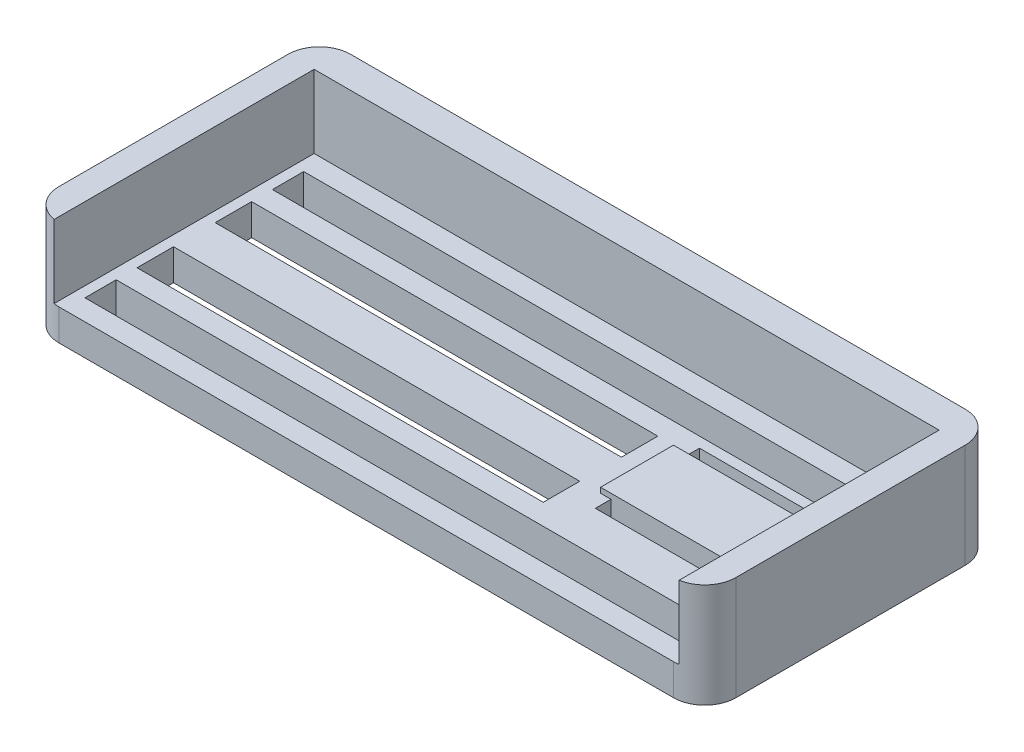
SolidWorks part; units mm, degrees
ref_plane "Front Plane" through (0, 0, 0) normal (0, 0, 1) x (1, 0, 0)
ref_plane "Top Plane" through (0, 0, 0) normal (0, 1, 0) x (1, 0, 0)
ref_plane "Right Plane" through (0, 0, 0) normal (1, 0, 0) x (0, 0, -1)
sketch "Sketch1" plane through (0, 0, 0) normal (0, 1, 0) x (1, 0, 0)
  line L1 (32.5, -14) -> (-32.5, -14)
  line L2 (32.5, -14) -> (32.5, 14)
  line L3 (32.5, 14) -> (-32.5, 14)
  line L4 (-32.5, -14) -> (-32.5, 14)
  line L5 (32.5, -14) -> (-32.5, 14) construction
  line L6 (32.5, 14) -> (-32.5, -14) construction
  point P0 (0, 0)
  dimension "D1" = 65
  dimension "D2" = 28
extrude "Boss-Extrude1" add sketch "Sketch1" along normal blind 10
sketch "Sketch2" plane through (0, 10, 0) normal (0, 1, 0) x (1, 0, 0)
  line L0 (-32.5, -14) -> (32.5, -14) construction
  line L2 (30, -11) -> (30, 11)
  line L3 (30, 11) -> (-30, 11)
  line L4 (-30, -11) -> (-30, 11)
  line L5 (30, -11) -> (-30, 11) construction
  line L6 (30, 11) -> (-30, -11) construction
  line L8 (-30, -11) -> (-30, -14)
  line L9 (-30, -14) -> (30, -14)
  line L10 (30, -11) -> (30, -14)
  point P0 (0, 0)
  dimension "D1" = 60
  dimension "D2" = 22
  dimension "D3" = 3
extrude "Cut-Extrude1" cut sketch "Sketch2" against normal blind 7
sketch "Sketch3" plane through (0, 3, 0) normal (0, 1, 0) x (1, 0, 0)
  line L0 (30, 0) -> (-30, 0) construction
  line L1 (30, -11) -> (-30, -11) construction
  line L2 (30, -11) -> (30, 11) construction
  line L3 (30, 11) -> (-30, 11) construction
  line L4 (-30, -11) -> (-30, 11) construction
  line L5 (30, -11) -> (-30, 11) construction
  line L6 (30, 11) -> (-30, -11) construction
  line L8 (23, -5) -> (13, -5)
  line L9 (23, -5) -> (23, 5)
  line L10 (23, 5) -> (13, 5)
  line L11 (13, -5) -> (13, 5)
  line L12 (23, -5) -> (13, 5) construction
  line L13 (23, 5) -> (13, -5) construction
  point P0 (0, 0)
  point P8 (18, 0)
  dimension "D1" = 60
  dimension "D2" = 22
  dimension "D3" = 10
  dimension "D4" = 10
  dimension "D5" = 7
extrude "Cut-Extrude2" cut sketch "Sketch3" against normal blind 7
ref_plane "Plane1" through (18, 0, 0) normal (1, 0, 0) x (0, 0, -1)
sketch "Sketch4" plane through (18, 0, 0) normal (1, 0, 0) x (0, 0, -1)
  line L0 (-3.5, -3.5) -> (-2.1213, -2.1213)
  line L2 (3.5, -3.5) -> (3.5, 3.5)
  line L3 (3.5, 3.5) -> (-3.5, 3.5)
  line L4 (-3.5, -3.5) -> (-3.5, 3.5)
  line L5 (3.5, -3.5) -> (-3.5, 3.5) construction
  line L6 (3.5, 3.5) -> (-3.5, -3.5) construction
  line L7 (2.1213, -2.1213) -> (3.5, -3.5)
  arc A0 (2.1213, -2.1213) -> (-2.1213, -2.1213) centre (0, 0) ccw
  point P0 (0, 0)
  dimension "D3" = 6
  dimension "D1" = 7
  dimension "D2" = 7
extrude "Boss-Extrude5" add sketch "Sketch4" along normal mid plane 12
sketch "Sketch5" plane through (23, 0, 0) normal (-1, 0, 0) x (0, 0, 1)
  line L2 (-2.8983, 0.1) -> (2.8983, 0.1)
  line L3 (-2.8983, 0.1) -> (2.8983, 0.1)
  arc A2 (2.8983, 0.1) -> (-2.8983, 0.1) centre (0, 0) ccw
  arc A3 (2.8983, 0.1) -> (-2.8983, 0.1) centre (0, 0) ccw
  dimension "D1" = 0.1
extrude "Cut-Extrude6" cut sketch "Sketch5" against normal blind 1
mirror "Mirror1" about plane through (18, 0, 0) normal (1, 0, 0) of "Cut-Extrude6"
sketch "Sketch6" plane through (0, 3, 0) normal (0, 1, 0) x (1, 0, 0)
  line L0 (30, -1.5) -> (-30, -1.5) construction
  line L1 (30, -14) -> (30, 11) construction
  line L2 (-30, 11) -> (-30, -14) construction
  line L3 (30, 11) -> (-30, 11) construction
  line L4 (-29, 9) -> (29, 9)
  line L5 (-29, 9) -> (-29, 6)
  line L6 (-29, 6) -> (29, 6)
  line L7 (29, 9) -> (29, 6)
  line L8 (-30, 11) -> (-30, -14) construction
  line L9 (30, -14) -> (30, 11) construction
  line L10 (23, 5) -> (13, 5) construction
  line L11 (12, 3.5) -> (12, -3.5) construction
  line L12 (-29, 4) -> (10, 4)
  line L13 (-29, 4) -> (-29, 0.5)
  line L14 (-29, 0.5) -> (10, 0.5)
  line L15 (10, 4) -> (10, 0.5)
  line L16 (-29, -3.5) -> (10, -3.5)
  line L17 (10, -7) -> (10, -3.5)
  line L18 (-29, -7) -> (10, -7)
  line L19 (-29, -7) -> (-29, -3.5)
  line L20 (-29, -9) -> (29, -9)
  line L21 (29, -12) -> (29, -9)
  line L22 (-29, -12) -> (29, -12)
  line L23 (-29, -12) -> (-29, -9)
  dimension "D1" = 2
  dimension "D2" = 1
  dimension "D3" = 1
  dimension "D4" = 1
  dimension "D5" = 2
  dimension "D6" = 2
  dimension "D7" = 2
  dimension "D8" = 1
extrude "Cut-Extrude7" cut sketch "Sketch6" against normal blind 41
fillet "Fillet1" radius 3 4 edges at (32.5, 5, 14) (-32.5, 5, 14) (-32.5, 5, -14) (32.5, 5, -14)
